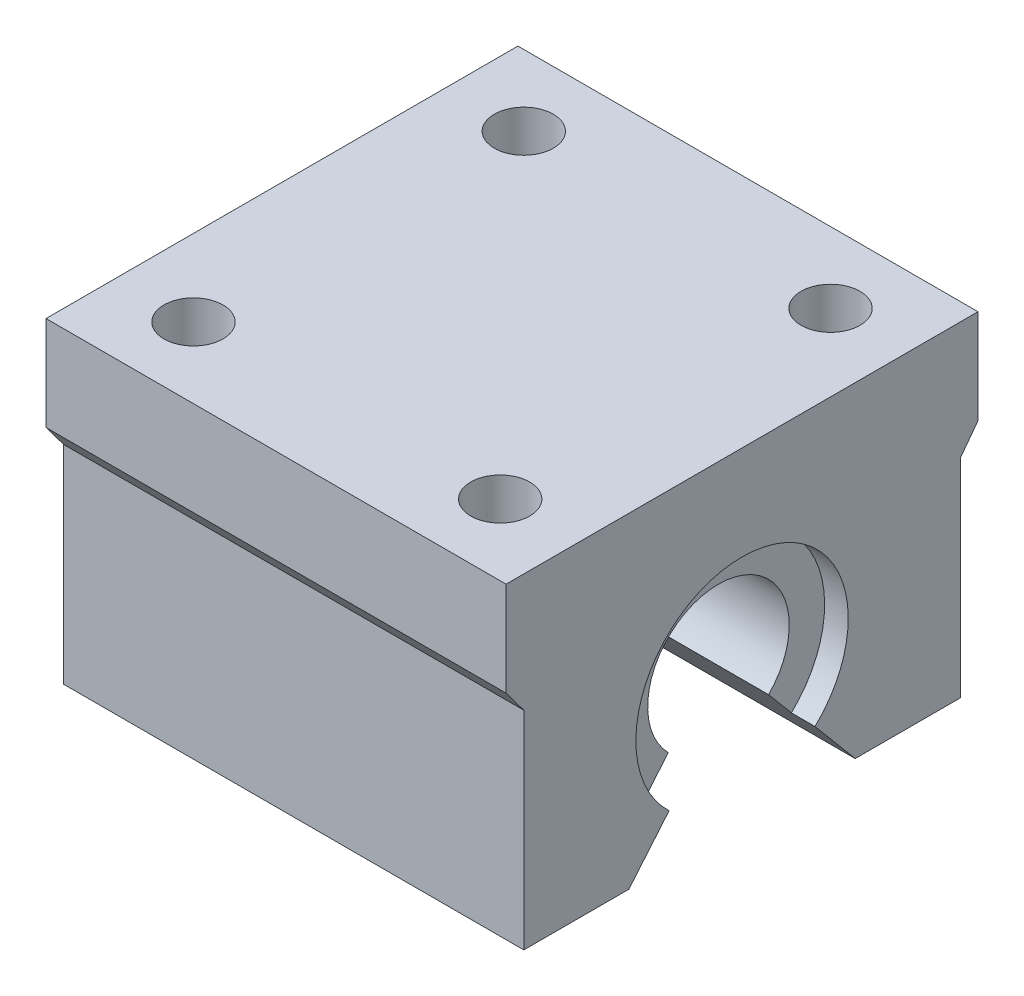
SolidWorks part; units mm, degrees
ref_plane "前视基准面" through (0, 0, 0) normal (0, 0, 1) x (1, 0, 0)
ref_plane "上视基准面" through (0, 0, 0) normal (0, 1, 0) x (1, 0, 0)
ref_plane "右视基准面" through (0, 0, 0) normal (1, 0, 0) x (0, 0, -1)
sketch "草图1" plane through (0, 0, 0) normal (1, 0, 0) x (0, 0, -1)
  line L0 (0, 10.6) -> (40, 10.6) construction
  line L1 (0, 0) -> (10.4094, 0)
  line L2 (0, 0) -> (0, 27.6)
  line L3 (0, 27.6) -> (40, 27.6)
  line L4 (40, 0) -> (40, 27.6)
  line L5 (20, 27.6) -> (20, -15.7281) construction
  line L6 (15.75, 6.3647) -> (24.25, 6.3647) construction
  line L9 (29.5906, 0) -> (40, 0)
  line L10 (15.75, 6.3647) -> (10.4094, 0)
  line L11 (24.25, 6.3647) -> (29.5906, 0)
  arc A0 (24.25, 6.3647) -> (15.75, 6.3647) centre (20, 10.6) ccw
  point P13 (20, 6.3647)
  dimension "D4" = 12
  dimension "D1" = 27.6
  dimension "D2" = 40
  dimension "D3" = 17
  dimension "D5" = 8.5
extrude "凸台-拉伸1" add sketch "草图1" along normal blind 39
ref_plane "基准面1" through (19.5, 0, 0) normal (1, 0, 0) x (0, 0, -1)
sketch "草图3" plane through (0, 0, 0) normal (-1, 0, 0) x (0, 0, 1)
  circle A0 centre (-20, 10.6) radius 9
  dimension "D1" = 18
extrude "切除-拉伸1" cut sketch "草图3" against normal blind 2
mirror "镜向1" about plane through (19.5, 0, 0) normal (1, 0, 0) of "切除-拉伸1"
sketch "草图4" plane through (0, 27.6, 0) normal (0, 1, 0) x (1, 0, 0)
  line L0 (0, 20) -> (39, 20) construction
  line L1 (0, 40) -> (0, 0) construction
  line L2 (39, 40) -> (39, 0) construction
  line L3 (19.5, 40) -> (19.5, 0) construction
  line L4 (39, 40) -> (0, 40) construction
  line L5 (39, 0) -> (0, 0) construction
  circle A0 centre (6.5, 6) radius 2.5
  circle A1 centre (6.5, 34) radius 2.5
  circle A2 centre (32.5, 6) radius 2.5
  circle A3 centre (32.5, 34) radius 2.5
  dimension "D1" = 5
  dimension "D2" = 26
  dimension "D3" = 28
extrude "切除-拉伸2" cut sketch "草图4" against normal blind 10
sketch "草图5" plane through (0, 0, 0) normal (-1, 0, 0) x (0, 0, 1)
  line L0 (0, 0) -> (-1.5, 0)
  line L1 (0, 0) -> (-10.4094, 0) construction
  line L2 (-1.5, 0) -> (-1.5, 17.6)
  line L3 (-1.5, 17.6) -> (0, 19.6)
  line L4 (0, 27.6) -> (0, 0) construction
  line L5 (0, 19.6) -> (0, 0)
  line L6 (-20, 27.6) -> (-20, 19.6) construction
  line L7 (-40, 27.6) -> (0, 27.6) construction
  line L8 (-40, 19.6) -> (-40, 0)
  line L9 (-40, 0) -> (-38.5, 0)
  line L10 (-38.5, 0) -> (-38.5, 17.6)
  line L11 (-38.5, 17.6) -> (-40, 19.6)
  arc A0 (-13.8165, 4.0605) -> (-26.1835, 4.0605) centre (-20, 10.6) ccw construction
  dimension "D1" = 8
  dimension "D2" = 1.5
  dimension "D3" = 2
extrude "切除-拉伸4" cut sketch "草图5" against normal through all
